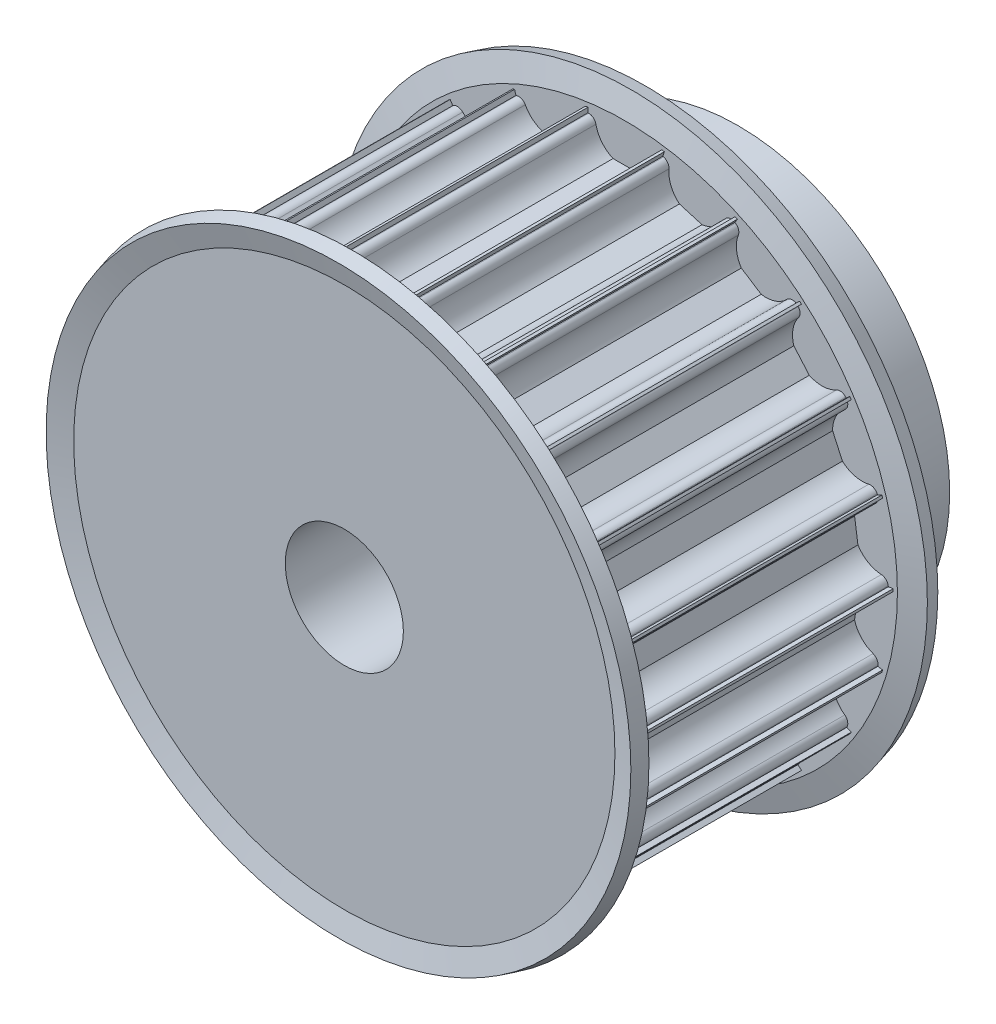
SolidWorks part; units mm, degrees
ref_plane "Front Plane" through (0, 0, 0) normal (0, 0, 1) x (1, 0, 0)
ref_plane "Top Plane" through (0, 0, 0) normal (0, 1, 0) x (1, 0, 0)
ref_plane "Right Plane" through (0, 0, 0) normal (1, 0, 0) x (0, 0, -1)
sketch "Sketch1" plane through (0, 0, 0) normal (1, 0, 0) x (0, 0, -1)
  line L0 (0, 0) -> (37.7698, 0) construction
  line L1 (0, 32.3741) -> (0, 6)
  line L2 (0, 6) -> (40, 6)
  line L3 (40, 6) -> (40, 21.5)
  line L4 (40, 21.5) -> (30, 21.5)
  line L5 (30, 21.5) -> (30, 27.25)
  line L6 (30, 27.25) -> (0, 27.25)
  line L7 (0, 27.25) -> (0, 32.3741)
  dimension "D1" = 30
  dimension "D2" = 6
  dimension "D3" = 27.25
  dimension "D4" = 15.5
  dimension "D5" = 10
revolve "Revolve2" add sketch "Sketch1" angle 360 about L0
sketch "Sketch2" plane through (0, 0, 0) normal (0, 0, 1) x (1, 0, 0)
  line L0 (-3.6742, 26.5) -> (-3.75, 26.5)
  line L1 (-3.75, 26.5) -> (-3.75, 28.5)
  line L2 (-3.75, 28.5) -> (3.75, 28.5)
  line L3 (3.75, 28.5) -> (3.75, 26.5)
  line L4 (3.75, 26.5) -> (3.6742, 26.5)
  line L5 (-1.199, 23.75) -> (1.199, 23.75)
  arc A0 (-2.9394, 25.9) -> (-1.199, 23.75) centre (0, 26.5) ccw
  arc A1 (-2.9394, 25.9) -> (-3.6742, 26.5) centre (-3.6742, 25.75) ccw
  arc A2 (2.9394, 25.9) -> (3.6742, 26.5) centre (3.6742, 25.75) cw
  arc A3 (1.199, 23.75) -> (2.9394, 25.9) centre (0, 26.5) ccw
  point P3 (0, 28.5)
  point P15 (0, 0)
  dimension "D1" = 3
  dimension "D5" = 0.75
  dimension "D6" = 0.75
  dimension "D2" = 26.5
  dimension "D3" = 2
  dimension "D4" = 7.5
  dimension "D7" = 2.75
extrude "Cut-Extrude1" cut sketch "Sketch2" against normal through all both and the other way through all
pattern_circular "CirPattern1" count 22 over 360 about axis through (0, 0, 0) along (0, 0, 1) of "Cut-Extrude1"
sketch "Sketch3" plane through (0, 0, 0) normal (1, 0, 0) x (0, 0, -1)
  line L0 (15, 0.1345) -> (15, 31.3594) construction
  line L1 (30, 0.1345) -> (0, 0.1345) construction
  line L2 (30, 21.5) -> (30, 27.4925)
  line L3 (30, 27.4925) -> (30.592, 29.7018)
  line L4 (30.592, 29.7018) -> (29.1431, 30.09)
  line L5 (29.1431, 30.09) -> (28.5, 27.69)
  line L6 (28.5, 27.69) -> (28.5, 21.5)
  line L7 (28.5, 21.5) -> (30, 21.5)
  line L8 (1.5, 27.69) -> (1.5, 21.5)
  line L9 (0.8569, 30.09) -> (1.5, 27.69)
  line L10 (-0.592, 29.7018) -> (0.8569, 30.09)
  line L11 (0, 27.4925) -> (-0.592, 29.7018)
  line L12 (0, 21.5) -> (0, 27.4925)
  line L13 (1.5, 21.5) -> (0, 21.5)
  line L14 (0, 0) -> (31.5704, 0) construction
  dimension "D1" = 1.5
  dimension "D2" = 6.19
  dimension "D3" = 15
  dimension "D4" = 2.4
revolve "Revolve3" add sketch "Sketch3" angle 360 about L14
